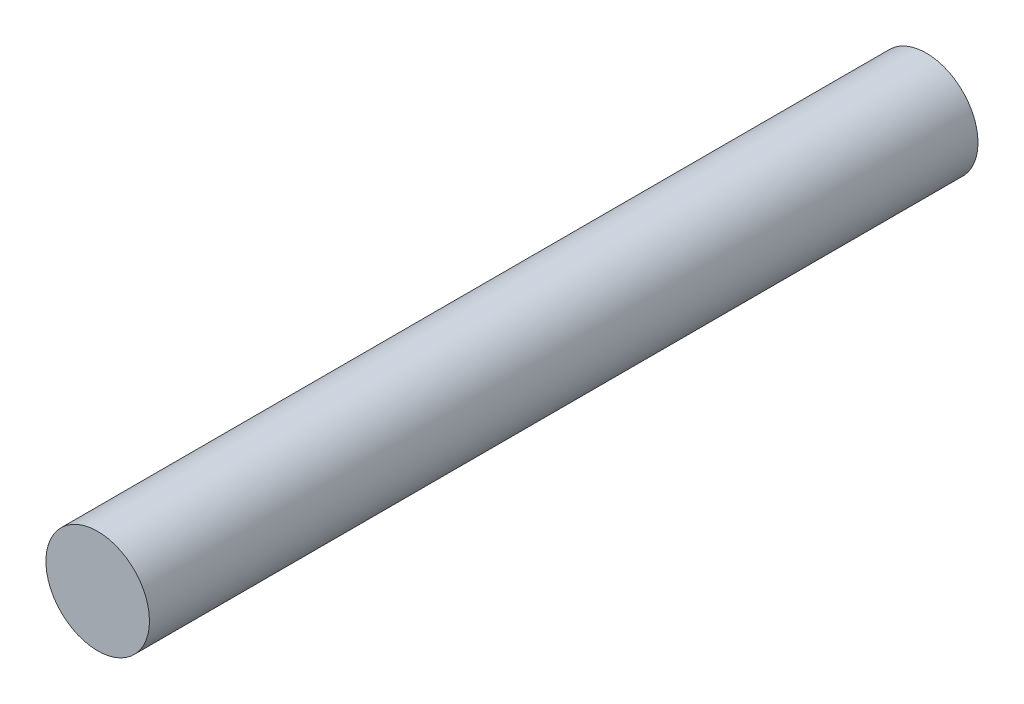
SolidWorks part; units mm, degrees
ref_plane "Front Plane" through (0, 0, 0) normal (0, 0, 1) x (1, 0, 0)
ref_plane "Top Plane" through (0, 0, 0) normal (0, 1, 0) x (1, 0, 0)
ref_plane "Right Plane" through (0, 0, 0) normal (1, 0, 0) x (0, 0, -1)
sketch "Sketch2" plane through (0, 0, 0) normal (0, 0, 1) x (1, 0, 0)
  circle A0 centre (0, 0) radius 3.175
  dimension "D1" = 6.35
extrude "Boss-Extrude1" add sketch "Sketch2" along normal blind 50.8
